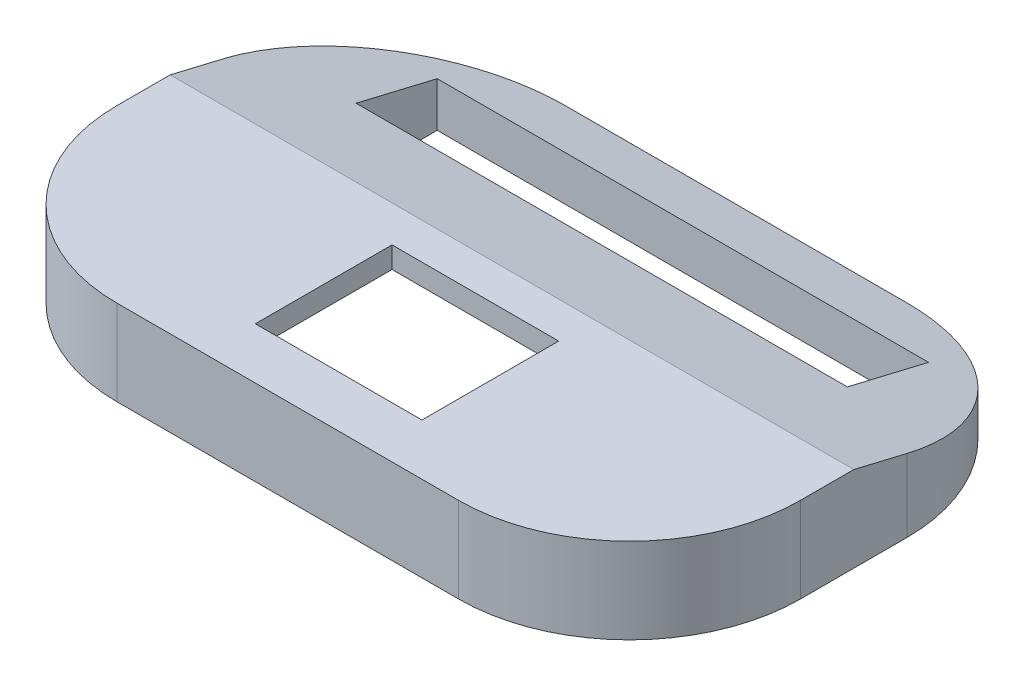
SolidWorks part; units mm, degrees
ref_plane "Front Plane" through (0, 0, 0) normal (0, 0, 1) x (1, 0, 0)
ref_plane "Top Plane" through (0, 0, 0) normal (0, 1, 0) x (1, 0, 0)
ref_plane "Right Plane" through (0, 0, 0) normal (1, 0, 0) x (0, 0, -1)
sketch "Sketch1" plane through (0, 0, 0) normal (0, 1, 0) x (1, 0, 0)
  line L1 (40, -52.5) -> (-40, -52.5)
  line L2 (80, -12.5) -> (80, 12.5)
  line L3 (40, 52.5) -> (-40, 52.5)
  line L4 (-80, -12.5) -> (-80, 12.5)
  arc A1 (-80, -12.5) -> (-40, -52.5) centre (-40, -12.5) ccw
  arc A2 (40, -52.5) -> (80, -12.5) centre (40, -12.5) ccw
  arc A3 (80, 12.5) -> (40, 52.5) centre (40, 12.5) ccw
  arc A4 (-40, 52.5) -> (-80, 12.5) centre (-40, 12.5) ccw
  point P0 (0, 0)
  dimension "D7" = 80
  dimension "D11" = 80
  dimension "D14" = 80
  dimension "D3" = 40
  dimension "D4" = 40
  dimension "D5" = 40
  dimension "D6" = 40
  dimension "D9" = 40
  dimension "D10" = 40
  dimension "D12" = 40
  dimension "D13" = 40
extrude "Boss-Extrude1" add sketch "Sketch1" along normal blind 20 contours A4 L4 A1 L1 A2 L2 A3 L3
sketch3d "3DSketch1" plane through (0, 0, 0) normal (0, 0, 1) x (1, 0, 0)
  dimension "D1" = 7.33
sketch "Sketch2" plane through (0, 27.33, 0) normal (0, 1, 0) x (1, 0, 0)
  line L0 (0, 0) -> (0, 52.5) construction
  line L1 (40, 52.5) -> (-40, 52.5) construction
  circle A0 centre (-55.4092, -15.65) radius 11.5
  circle A2 centre (56.9957, -15.075) radius 11.5
  dimension "D1" = 23
  dimension "D2" = 23
sketch "Sketch4" plane through (0, 20, 0) normal (0, 1, 0) x (1, 0, 0)
  circle A0 centre (-55.4092, -15.65) radius 16
  circle A1 centre (56.9957, -15.075) radius 16
  dimension "D1" = 32
  dimension "D2" = 32
sketch3d "3DSketch3"
sketch "Sketch5" plane through (0, 20, 0) normal (0, 1, 0) x (1, 0, 0)
  line L1 (19.4207, -40.5) -> (-19.5793, -40.5)
  line L2 (19.4207, -40.5) -> (19.4207, -8.5)
  line L3 (19.4207, -8.5) -> (-19.5793, -8.5)
  line L4 (-19.5793, -40.5) -> (-19.5793, -8.5)
  line L5 (40, -52.5) -> (-40, -52.5) construction
  dimension "D1" = 39
  dimension "D2" = 32
  dimension "D3" = 19.5
  dimension "D4" = 12
extrude "Cut-Extrude1" cut sketch "Sketch5" against normal through all
sketch "Sketch6" plane through (0, 0, 0) normal (0, -1, 0) x (1, 0, 0)
  line L0 (-19.5793, 8.5) -> (-19.5793, 40.5) construction
  line L1 (-29.5793, 43.4957) -> (29.4207, 43.4957)
  line L2 (-29.5793, 43.4957) -> (-29.5793, -11.5)
  line L3 (-29.5793, -11.5) -> (29.4207, -11.5)
  line L4 (29.4207, 43.4957) -> (29.4207, -11.5)
  line L5 (19.4207, 40.5) -> (19.4207, 8.5) construction
  line L6 (19.4207, 8.5) -> (-19.5793, 8.5) construction
  dimension "D1" = 10
  dimension "D2" = 10
  dimension "D3" = 20
extrude "Cut-Extrude2" cut sketch "Sketch6" against normal blind 15
sketch "Sketch7" plane through (0, 0, 0) normal (0, -1, 0) x (1, 0, 0)
  line L1 (57.5, -40) -> (-57.5, -40)
  line L2 (57.5, -40) -> (57.5, 40)
  line L3 (57.5, 40) -> (-57.5, 40)
  line L4 (-57.5, -40) -> (-57.5, 40)
  line L5 (57.5, -40) -> (-57.5, 40) construction
  line L6 (57.5, 40) -> (-57.5, -40) construction
  point P0 (0, 0)
  dimension "D1" = 115
  dimension "D2" = 80
extrude "Cut-Extrude3" cut sketch "Sketch7" against normal blind 15
sketch "Sketch8" plane through (80, 0, 0) normal (1, 0, 0) x (0, 0, -1)
  line L0 (0, 20) -> (52.5, 7.5)
  line L1 (-12.5, 20) -> (12.5, 20) construction
  line L2 (52.5, 20) -> (52.5, 0) construction
  line L3 (52.5, 7.5) -> (52.5, 0)
  line L4 (52.5, 0) -> (-27.5, 0)
  line L5 (-52.5, 0) -> (-12.5, 0) construction
  line L7 (-12.5, 20) -> (-52.5, 20) construction
  line L8 (-27.5, 20) -> (0, 20)
  line L9 (-52.5, 20) -> (-27.5, 20)
  line L10 (-52.5, 0) -> (-52.5, 20)
  line L11 (-27.5, 0) -> (-52.5, 0)
  dimension "D1" = 80
  dimension "D2" = 7.5
extrude "Cut-Extrude4" cut sketch "Sketch8" against normal through all flip side to cut
